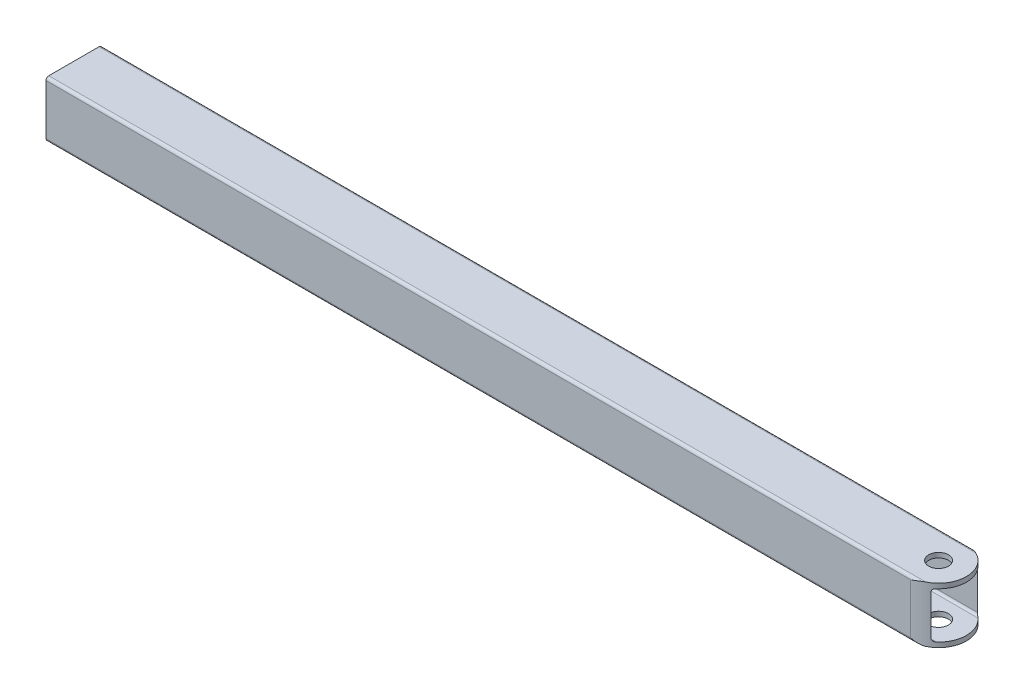
SolidWorks part; units mm, degrees
ref_plane "Front" through (0, 0, 0) normal (0, 0, 1) x (1, 0, 0)
ref_plane "Top" through (0, 0, 0) normal (0, 1, 0) x (1, 0, 0)
ref_plane "Right" through (0, 0, 0) normal (1, 0, 0) x (0, 0, -1)
sketch "Sketch1" plane through (0, 0, 0) normal (1, 0, 0) x (0, 0, -1)
  line L0 (-7.874, 0) -> (-9.525, 0) construction
  line L1 (8.5725, -9.525) -> (-8.5725, -9.525) construction
  line L2 (9.525, -8.5725) -> (9.525, 8.5725) construction
  line L3 (8.5725, 9.525) -> (-8.5725, 9.525) construction
  line L4 (-9.525, -8.5725) -> (-9.525, 8.5725) construction
  line L5 (9.525, -9.525) -> (-9.525, 9.525) construction
  line L6 (9.525, 9.525) -> (-9.525, -9.525) construction
  line L7 (7.0866, 7.874) -> (-7.0866, 7.874) construction
  line L8 (7.874, 7.0866) -> (7.874, -7.0866) construction
  line L9 (7.0866, -7.874) -> (-7.0866, -7.874) construction
  line L10 (-7.874, 7.0866) -> (-7.874, -7.0866) construction
  line L11 (7.874, 7.874) -> (-7.874, -7.874) construction
  line L12 (7.874, -7.874) -> (-7.874, 7.874) construction
  line L13 (0, -7.874) -> (0, -9.525) construction
  line L14 (7.874, -7.0866) -> (7.874, -9.525) construction
  line L15 (7.874, 0) -> (9.525, 0) construction
  line L16 (7.874, -9.525) -> (9.525, -9.525) construction
  arc A0 (-7.0866, -7.874) -> (-7.874, -7.0866) centre (-7.0866, -7.0866) cw construction
  arc A1 (7.874, -7.0866) -> (7.0866, -7.874) centre (7.0866, -7.0866) cw construction
  arc A2 (7.0866, 7.874) -> (7.874, 7.0866) centre (7.0866, 7.0866) cw construction
  arc A3 (-7.0866, 7.874) -> (-7.874, 7.0866) centre (-7.0866, 7.0866) ccw construction
  arc A4 (8.5725, -9.525) -> (9.525, -8.5725) centre (8.5725, -8.5725) ccw construction
  arc A5 (9.525, 8.5725) -> (8.5725, 9.525) centre (8.5725, 8.5725) ccw construction
  arc A6 (-8.5725, 9.525) -> (-9.525, 8.5725) centre (-8.5725, 8.5725) ccw construction
  arc A7 (-8.5725, -9.525) -> (-9.525, -8.5725) centre (-8.5725, -8.5725) cw construction
  point P0 (0, 0)
  point P6 (0, 0)
  dimension "D2" = 0.7874
  dimension "D3" = 0.9525
  dimension "Outside Width" = 19.05
  dimension "Ouside Height" = 19.05
  dimension "Inside Height" = 15.748
  dimension "Wall Thickness" = 1.651
sketch "Sketch2" plane through (0, 0, 0) normal (0, 0, 1) x (1, 0, 0)
  line L0 (-152.4, 0) -> (152.4, 0) construction
  point P3 (-135.001, 0)
  point P4 (135.001, 0)
  dimension "Length" = 304.8
  dimension "D1" = 17.399
  dimension "D2" = 17.399
sketch "Sketch4" plane through (0, 0, 0) normal (1, 0, 0) x (0, 0, -1)
  line L8 (9.525, -8.5725) -> (9.525, 8.5725)
  line L9 (8.5725, 9.525) -> (-8.5725, 9.525)
  line L10 (-9.525, -8.5725) -> (-9.525, 8.5725)
  line L11 (8.5725, -9.525) -> (-8.5725, -9.525)
  line L12 (7.874, 7.0866) -> (7.874, -7.0866)
  line L13 (7.0866, -7.874) -> (-7.0866, -7.874)
  line L14 (-7.874, 7.0866) -> (-7.874, -7.0866)
  line L15 (7.0866, 7.874) -> (-7.0866, 7.874)
  arc A8 (9.525, 8.5725) -> (8.5725, 9.525) centre (8.5725, 8.5725) ccw
  arc A9 (-8.5725, 9.525) -> (-9.525, 8.5725) centre (-8.5725, 8.5725) ccw
  arc A10 (-9.525, -8.5725) -> (-8.5725, -9.525) centre (-8.5725, -8.5725) ccw
  arc A11 (8.5725, -9.525) -> (9.525, -8.5725) centre (8.5725, -8.5725) ccw
  arc A12 (7.0866, -7.874) -> (7.874, -7.0866) centre (7.0866, -7.0866) ccw
  arc A13 (-7.874, -7.0866) -> (-7.0866, -7.874) centre (-7.0866, -7.0866) ccw
  arc A14 (-7.0866, 7.874) -> (-7.874, 7.0866) centre (-7.0866, 7.0866) ccw
  arc A15 (7.874, 7.0866) -> (7.0866, 7.874) centre (7.0866, 7.0866) ccw
extrude "Boss-Extrude1" add sketch "Sketch4" along normal up to vertex (152.4 mm away) and the other way up to vertex (152.4 mm away)
sketch "Sketch5" plane through (0, -9.525, 0) normal (0, -1, 0) x (1, 0, 0)
  line L0 (152.4, -9.525) -> (-152.4, -9.525) construction
  line L1 (152.4, 9.525) -> (-152.4, 9.525) construction
  line L2 (152.4, -9.525) -> (142.875, -9.525)
  line L3 (152.4, 9.525) -> (142.875, 9.525)
  line L4 (152.4, 8.5725) -> (152.4, -8.5725) construction
  line L5 (152.4, 9.525) -> (157.48, 9.525)
  line L6 (157.48, 9.525) -> (157.48, -9.525)
  line L7 (157.48, -9.525) -> (152.4, -9.525)
  arc A0 (142.875, 9.525) -> (142.875, -9.525) centre (142.875, 0) cw
  dimension "D1" = 5.08
extrude "Cut-Extrude1" cut sketch "Sketch5" against normal through all
sketch "Sketch6" plane through (0, 9.525, 0) normal (0, 1, 0) x (1, 0, 0)
  circle A0 centre (142.875, 0) radius 3.3782
  arc A1 (147.0269, -8.5725) -> (147.0269, 8.5725) centre (142.875, 0) ccw construction
  dimension "D1" = 6.7564
extrude "Cut-Extrude2" cut sketch "Sketch6" against normal through all
equation "\"D3@Sketch1\"=\"Outside Width@Sketch1\"*.05"
equation "\"D2@Sketch1\" = \"Inside Height@Sketch1\" * .05"
equation "\"D1@Sketch2\"=\"Outside Width@Sketch1\"-\"Wall Thickness@Sketch1\""
equation "\"D2@Sketch2\"=\"D1@Sketch2\""
